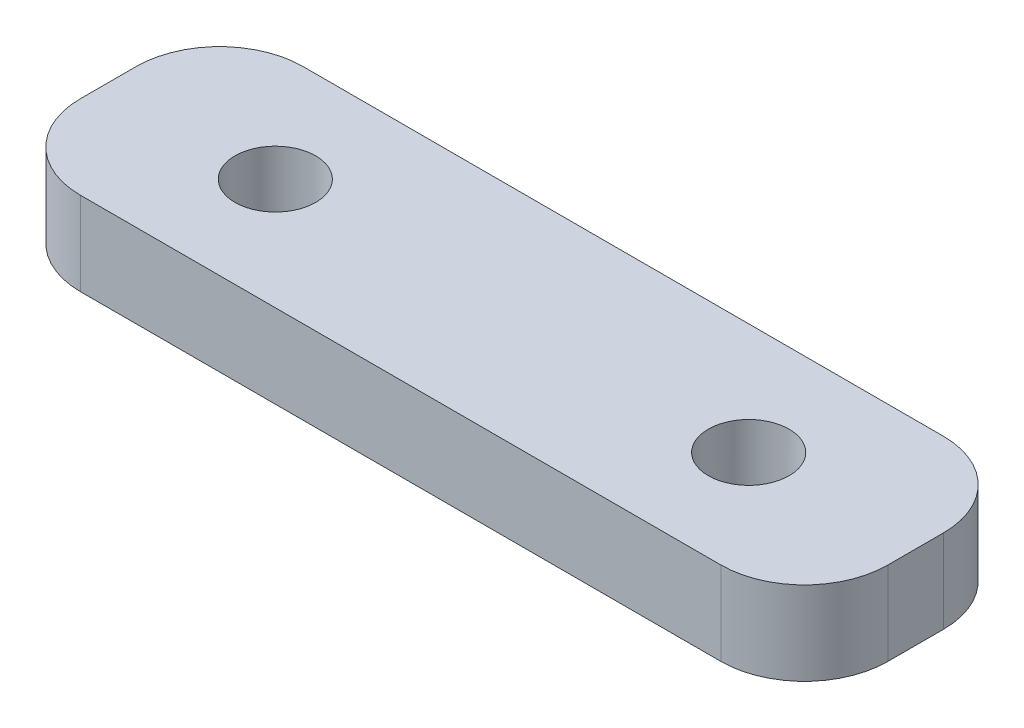
SolidWorks part; units mm, degrees
material "Perspex (TM) GS Acrylic Cast Sheet"
ref_plane "Front Plane" through (0, 0, 0) normal (0, 0, 1) x (1, 0, 0)
ref_plane "Top Plane" through (0, 0, 0) normal (0, 1, 0) x (1, 0, 0)
ref_plane "Right Plane" through (0, 0, 0) normal (1, 0, 0) x (0, 0, -1)
sketch "Sketch1" plane through (0, 0, 0) normal (0, 1, 0) x (1, 0, 0)
  line L1 (0, 0) -> (29, 0)
  line L2 (0, 0) -> (0, 8)
  line L3 (0, 8) -> (29, 8)
  line L4 (29, 0) -> (29, 8)
  dimension "D1" = 29
  dimension "D2" = 8
extrude "Boss-Extrude1" add sketch "Sketch1" along normal blind 3
hole_wizard "M2.5 Clearance Hole1" positions "Sketch3" profile "Sketch2" hole size "M2.5" standard "ISO" end condition up to next
sketch "Sketch3" plane through (0, 3, 0) normal (0, 1, 0) x (1, 0, 0)
  line L0 (29, 0) -> (29, 8) construction
  line L1 (0, 0) -> (29, 0) construction
  point P0 (6, 4)
  point P2 (23, 4)
  dimension "D1" = 17
  dimension "D2" = 6
  dimension "D3" = 4
sketch "Sketch2" plane through (6, 3, -4) normal (1, 0, 0) x (0, 0, 1)
  line L0 (0, 0) -> (0, 3)
  line L1 (0, 3) -> (1.45, 3)
  line L2 (1.45, 3) -> (1.45, 0)
  line L5 (1.45, 0) -> (0, 0)
  line L11 (0, -6.35) -> (0, 107.95) construction
  dimension "Thru Hole Dia." = 2.9
  dimension "Thru Hole Depth" = 3
fillet "Fillet1" radius 3 4 edges at (0, 1.5, -8) (0, 1.5, 0) (29, 1.5, 0) (29, 1.5, -8)
sketch "Sketch4" plane through (0, 0, 0) normal (0, 0, 1) x (1, 0, 0)
  line L0 (3, 3) -> (26, 3) construction
  circle A0 centre (14.5, 3) radius 5
  point P4 (14.5, 3)
  dimension "D1" = 10
